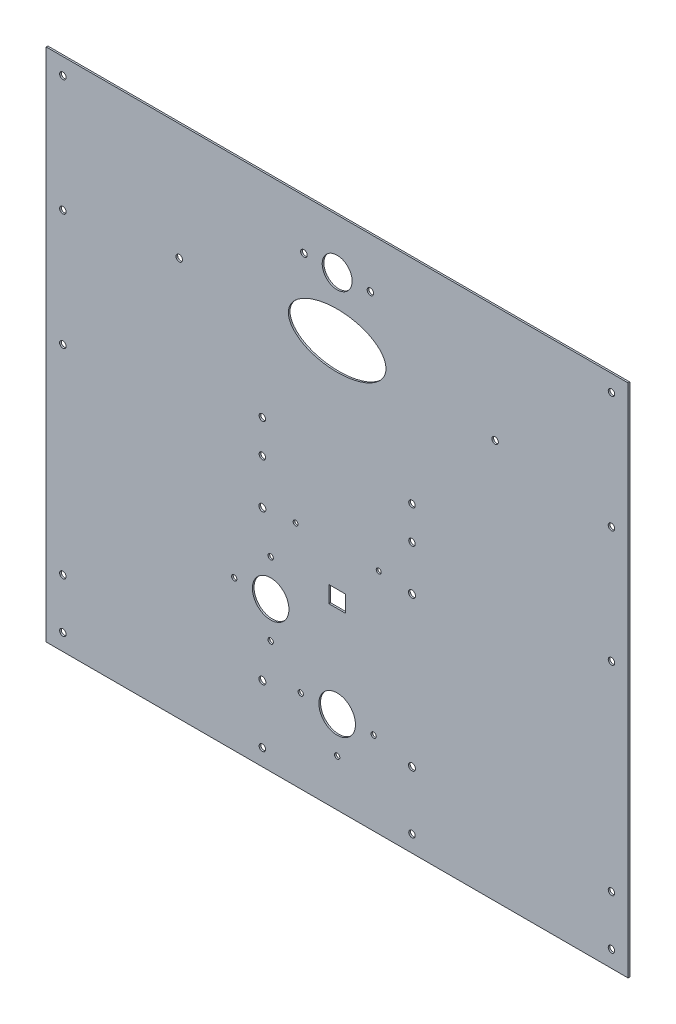
SolidWorks part; units mm, degrees
ref_plane "前视基准面" through (0, 0, 0) normal (0, 0, 1) x (1, 0, 0)
ref_plane "上视基准面" through (0, 0, 0) normal (0, 1, 0) x (1, 0, 0)
ref_plane "右视基准面" through (0, 0, 0) normal (1, 0, 0) x (0, 0, -1)
sketch "草图1" plane through (0, 0, 0) normal (0, 0, 1) x (1, 0, 0)
  line L1 (0, 0) -> (350, 0)
  line L2 (0, 0) -> (0, 310)
  line L3 (0, 310) -> (350, 310)
  line L4 (350, 0) -> (350, 310)
  circle A0 centre (10, 300) radius 1.95
  circle A1 centre (10, 230) radius 1.95
  circle A2 centre (10, 40) radius 1.95
  circle A3 centre (10, 10) radius 1.95
  circle A4 centre (340, 300) radius 1.95
  circle A5 centre (340, 230) radius 1.95
  circle A6 centre (340, 40) radius 1.95
  circle A7 centre (340, 10) radius 1.95
  circle A8 centre (130, 10) radius 1.95
  circle A10 centre (220, 10) radius 1.95
  circle A11 centre (10, 160) radius 1.95
  circle A12 centre (340, 160) radius 1.95
  circle A13 centre (130, 162) radius 1.95
  circle A14 centre (220, 162) radius 1.95
  circle A15 centre (175, 280) radius 9
  circle A16 centre (130, 182) radius 1.95
  circle A17 centre (220, 182) radius 1.95
  circle A18 centre (80, 240) radius 1.95
  circle A19 centre (270, 240) radius 1.95
  circle A20 centre (155, 280) radius 1.95
  circle A21 centre (195, 280) radius 1.95
  point P34 (175, 310)
  dimension "D8" = 3.9
  dimension "D17" = 18
  dimension "D1" = 350
  dimension "D2" = 310
  dimension "D3" = 10
  dimension "D4" = 10
  dimension "D5" = 10
  dimension "D6" = 10
  dimension "D7" = 70
  dimension "D9" = 30
  dimension "D10" = 120
  dimension "D11" = 120
  dimension "D12" = 70
  dimension "D13" = 90
  dimension "D14" = 120
  dimension "D16" = 30
  dimension "D18" = 20
  dimension "D19" = 70
  dimension "D20" = 80
  dimension "D21" = 80
  dimension "D22" = 20
  dimension "D23" = 20
extrude "凸台-拉伸1" add sketch "草图1" along normal blind 1
sketch "草图2" plane through (0, 0, 0) normal (0, 0, -1) x (-1, 0, 0)
  line L1 (0, 0) -> (-350, 0) construction
  line L2 (-170, 105) -> (-180, 105)
  line L3 (-170, 105) -> (-170, 115)
  line L4 (-170, 115) -> (-180, 115)
  line L5 (-180, 105) -> (-180, 115)
  circle A0 centre (-130, 135) radius 2.1
  circle A2 centre (-220, 45) radius 2.1
  circle A4 centre (-220, 135) radius 2.1
  circle A8 centre (-130, 45) radius 2.1
  circle A10 centre (-153.0797, 50) radius 1.6
  circle A12 centre (-175, 28.0797) radius 1.6
  circle A14 centre (-196.9203, 50) radius 1.6
  circle A16 centre (-175, 50) radius 11
  circle A17 centre (-150, 137) radius 1.5
  circle A18 centre (-135, 90) radius 11
  circle A20 centre (-200, 137) radius 1.5
  circle A21 centre (-113.0797, 90) radius 1.6
  circle A22 centre (-135, 68.0797) radius 1.6
  circle A23 centre (-135, 111.9203) radius 1.6
  point P23 (-175, 0)
  dimension "D11" = 3
  dimension "D12" = 10
extrude "切除-拉伸1" cut sketch "草图2" against normal blind 10
sketch "草图3" plane through (0, 0, 1) normal (0, 0, 1) x (1, 0, 0)
  line L0 (175, 215.5349) -> (175, 251.6927) construction
  ellipse E0 centre (175, 244.535) end of major axis (204.3541, 244.535) minor radius 16.4892
extrude "切除-拉伸2" cut sketch "草图3" against normal blind 8
